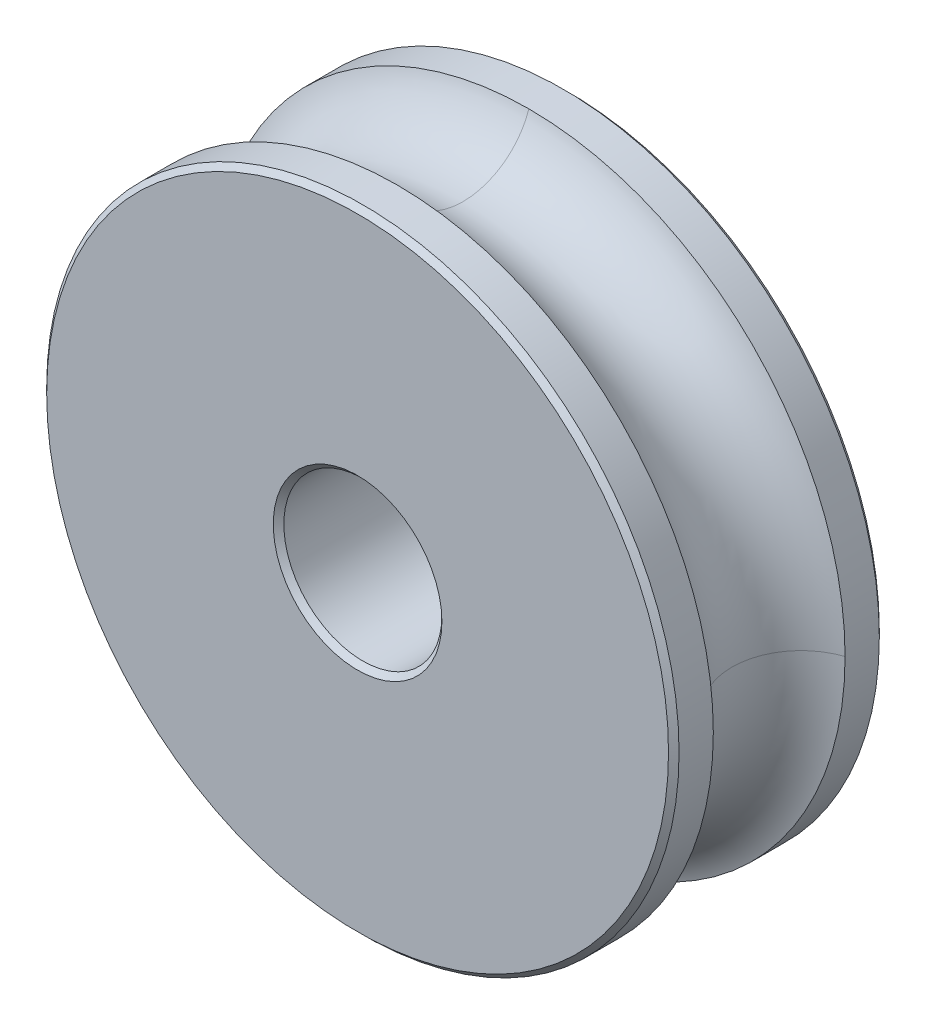
SolidWorks part; units mm, degrees
ref_plane "前视基准面" through (0, 0, 0) normal (0, 0, 1) x (1, 0, 0)
ref_plane "上视基准面" through (0, 0, 0) normal (0, 1, 0) x (1, 0, 0)
ref_plane "右视基准面" through (0, 0, 0) normal (1, 0, 0) x (0, 0, -1)
sketch "草图1" plane through (0, 0, 0) normal (0, 0, 1) x (1, 0, 0)
  circle A0 centre (0, 0) radius 1.5
  circle A1 centre (0, 0) radius 6
  dimension "D1" = 3
  dimension "D2" = 12
extrude "凸台-拉伸1" add sketch "草图1" along normal mid plane 4
sketch "草图2" plane through (0, 0, 0) normal (1, 0, 0) x (0, 0, -1)
  line L3 (-1.25, 6) -> (1.25, 6)
  line L4 (2, 6) -> (-2, 6) construction
  arc A0 (-1.25, 6) -> (1.25, 6) centre (0, 6.4181) ccw
  point P6 (0, 5.5537)
  point P9 (0, 5.1)
  dimension "D1" = 2.5
  dimension "D2" = 0.9
sweep "切除-扫描1" cut profiles "草图2" path edge at (6, 0, -2)
chamfer "倒角1" distance 0.1 angle 45 4 edges at (6, 0, -2) (6, 0, 2) (1.5, 0, 2) (1.5, 0, -2)
